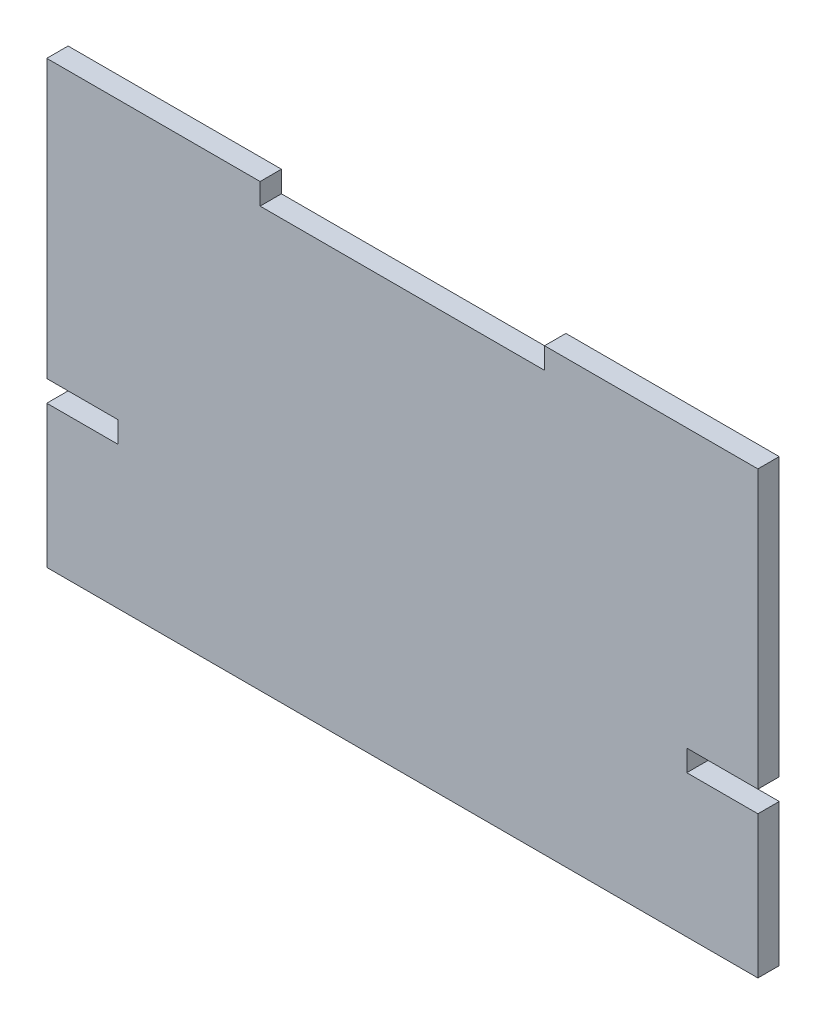
SolidWorks part; units mm, degrees
ref_plane "Front Plane" through (0, 0, 0) normal (0, 0, 1) x (1, 0, 0)
ref_plane "Top Plane" through (0, 0, 0) normal (0, 1, 0) x (1, 0, 0)
ref_plane "Right Plane" through (0, 0, 0) normal (1, 0, 0) x (0, 0, -1)
sketch "Sketch1" plane through (0, 0, 0) normal (0, 0, 1) x (1, 0, 0)
  line L0 (-20, 31) -> (-20, 28)
  line L1 (50, -31) -> (-50, -31)
  line L2 (50, -31) -> (50, -11)
  line L3 (50, 31) -> (20, 31)
  line L4 (-50, -31) -> (-50, -11)
  line L5 (50, -31) -> (-50, 31) construction
  line L6 (50, 31) -> (-50, -31) construction
  line L7 (-20, 28) -> (20, 28)
  line L8 (20, 28) -> (20, 31)
  line L9 (-20, 31) -> (-50, 31)
  line L10 (-50, -11) -> (-40, -11)
  line L11 (-40, -11) -> (-40, -8)
  line L12 (-40, -8) -> (-50, -8)
  line L13 (-50, -8) -> (-50, 31)
  line L15 (40, -8) -> (50, -8)
  line L16 (40, -11) -> (40, -8)
  line L17 (50, -11) -> (40, -11)
  line L18 (50, -8) -> (50, 31)
  point P0 (0, 0)
  dimension "D1" = 62
  dimension "D2" = 100
  dimension "D3" = 30
  dimension "D4" = 40
  dimension "D5" = 3
  dimension "D6" = 20
  dimension "D7" = 3
  dimension "D8" = 10
extrude "Boss-Extrude1" add sketch "Sketch1" along normal blind 3
